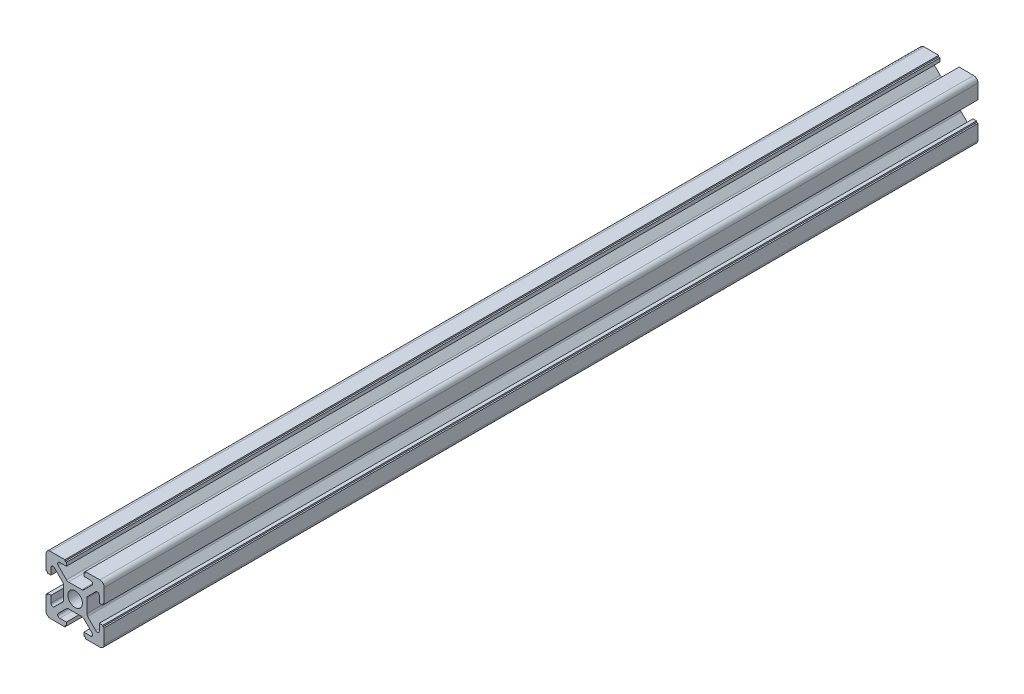
SolidWorks part; units mm, degrees
ref_plane "前视基准面" through (0, 0, 0) normal (0, 0, 1) x (1, 0, 0)
ref_plane "上视基准面" through (0, 0, 0) normal (0, 1, 0) x (1, 0, 0)
ref_plane "右视基准面" through (0, 0, 0) normal (1, 0, 0) x (0, 0, -1)
sketch "草图1" plane through (0, 0, 0) normal (0, 0, 1) x (1, 0, 0)
  line L112 (173.5, -150) -> (168.5, -150)
  line L113 (168.5, -150) -> (168.5, -150.5)
  line L114 (168.5, -150.5) -> (168, -150.5)
  line L115 (168, -150.5) -> (168, -151.7)
  line L116 (168, -151.7) -> (170.2994, -151.7)
  line L117 (170.7944, -152.895) -> (167.1755, -156.5139)
  line L118 (165.3, -156.262) -> (165, -156.55)
  line L119 (165, -156.55) -> (164.7, -156.262)
  line L120 (162.8245, -156.5139) -> (159.2056, -152.895)
  line L121 (159.7006, -151.7) -> (162, -151.7)
  line L122 (162, -151.7) -> (162, -150.5)
  line L123 (162, -150.5) -> (161.5, -150.5)
  line L124 (161.5, -150.5) -> (161.5, -150)
  line L125 (161.5, -150) -> (156.5, -150)
  line L126 (155, -151.5) -> (155, -156.5)
  line L127 (155, -156.5) -> (155.5, -156.5)
  line L128 (155.5, -156.5) -> (155.5, -157)
  line L129 (155.5, -157) -> (156.7, -157)
  line L130 (156.7, -157) -> (156.7, -154.7006)
  line L131 (157.895, -154.2056) -> (161.5139, -157.8245)
  line L132 (161.262, -159.7) -> (161.55, -160)
  line L133 (161.55, -160) -> (161.262, -160.3)
  line L134 (161.5139, -162.1755) -> (157.895, -165.7944)
  line L135 (156.7, -165.2994) -> (156.7, -163)
  line L136 (156.7, -163) -> (155.5, -163)
  line L137 (155.5, -163) -> (155.5, -163.5)
  line L138 (155.5, -163.5) -> (155, -163.5)
  line L139 (155, -163.5) -> (155, -168.5)
  line L140 (156.5, -170) -> (161.5, -170)
  line L141 (161.5, -170) -> (161.5, -169.5)
  line L142 (161.5, -169.5) -> (162, -169.5)
  line L143 (162, -169.5) -> (162, -168.3)
  line L144 (162, -168.3) -> (159.7006, -168.3)
  line L145 (159.2056, -167.105) -> (162.8245, -163.4861)
  line L146 (164.7, -163.738) -> (165, -163.45)
  line L147 (165, -163.45) -> (165.3, -163.738)
  line L148 (167.1755, -163.4861) -> (170.7944, -167.105)
  line L149 (170.2994, -168.3) -> (168, -168.3)
  line L150 (168, -168.3) -> (168, -169.5)
  line L151 (168, -169.5) -> (168.5, -169.5)
  line L152 (168.5, -169.5) -> (168.5, -170)
  line L153 (168.5, -170) -> (173.5, -170)
  line L154 (175, -168.5) -> (175, -163.5)
  line L155 (175, -163.5) -> (174.5, -163.5)
  line L156 (174.5, -163.5) -> (174.5, -163)
  line L157 (174.5, -163) -> (173.3, -163)
  line L158 (173.3, -163) -> (173.3, -165.2994)
  line L159 (172.105, -165.7944) -> (168.4861, -162.1755)
  line L160 (168.738, -160.3) -> (168.45, -160)
  line L161 (168.45, -160) -> (168.738, -159.7)
  line L162 (168.4861, -157.8245) -> (172.105, -154.2056)
  line L163 (173.3, -154.7006) -> (173.3, -157)
  line L164 (173.3, -157) -> (174.5, -157)
  line L165 (174.5, -157) -> (174.5, -156.5)
  line L166 (174.5, -156.5) -> (175, -156.5)
  line L167 (175, -156.5) -> (175, -151.5)
  circle A0 centre (165, -160) radius 2.5
  arc A56 (170.7944, -152.895) -> (170.2994, -151.7) centre (170.2994, -152.4) ccw
  arc A57 (166.6076, -156.612) -> (167.1755, -156.5139) centre (166.8219, -156.1603) ccw
  arc A58 (166.6076, -156.612) -> (165.3, -156.262) centre (165, -160) ccw
  arc A59 (164.7, -156.262) -> (163.3924, -156.612) centre (165, -160) ccw
  arc A60 (162.8245, -156.5139) -> (163.3924, -156.612) centre (163.1781, -156.1603) ccw
  arc A61 (159.7006, -151.7) -> (159.2056, -152.895) centre (159.7006, -152.4) ccw
  arc A62 (156.5, -150) -> (155, -151.5) centre (156.5, -151.5) ccw
  arc A63 (157.895, -154.2056) -> (156.7, -154.7006) centre (157.4, -154.7006) ccw
  arc A64 (161.612, -158.3924) -> (161.5139, -157.8245) centre (161.1603, -158.1781) ccw
  arc A65 (161.612, -158.3924) -> (161.262, -159.7) centre (165, -160) ccw
  arc A66 (161.262, -160.3) -> (161.612, -161.6076) centre (165, -160) ccw
  arc A67 (161.5139, -162.1755) -> (161.612, -161.6076) centre (161.1603, -161.8219) ccw
  arc A68 (156.7, -165.2994) -> (157.895, -165.7944) centre (157.4, -165.2994) ccw
  arc A69 (155, -168.5) -> (156.5, -170) centre (156.5, -168.5) ccw
  arc A70 (159.2056, -167.105) -> (159.7006, -168.3) centre (159.7006, -167.6) ccw
  arc A71 (163.3924, -163.388) -> (162.8245, -163.4861) centre (163.1781, -163.8397) ccw
  arc A72 (163.3924, -163.388) -> (164.7, -163.738) centre (165, -160) ccw
  arc A73 (165.3, -163.738) -> (166.6076, -163.388) centre (165, -160) ccw
  arc A74 (167.1755, -163.4861) -> (166.6076, -163.388) centre (166.8219, -163.8397) ccw
  arc A75 (170.2994, -168.3) -> (170.7944, -167.105) centre (170.2994, -167.6) ccw
  arc A76 (173.5, -170) -> (175, -168.5) centre (173.5, -168.5) ccw
  arc A77 (172.105, -165.7944) -> (173.3, -165.2994) centre (172.6, -165.2994) ccw
  arc A78 (168.388, -161.6076) -> (168.4861, -162.1755) centre (168.8397, -161.8219) ccw
  arc A79 (168.388, -161.6076) -> (168.738, -160.3) centre (165, -160) ccw
  arc A80 (168.738, -159.7) -> (168.388, -158.3924) centre (165, -160) ccw
  arc A81 (168.4861, -157.8245) -> (168.388, -158.3924) centre (168.8397, -158.1781) ccw
  arc A82 (173.3, -154.7006) -> (172.105, -154.2056) centre (172.6, -154.7006) ccw
  arc A83 (175, -151.5) -> (173.5, -150) centre (173.5, -151.5) ccw
extrude "凸台-拉伸1" add sketch "草图1" along normal blind 300
sketch "草图2" plane through (0, 0, 300) normal (0, 0, 1) x (1, 0, 0)
  line L1 (161, -156) -> (169, -156)
  line L2 (161, -156) -> (161, -164)
  line L3 (161, -164) -> (169, -164)
  line L4 (169, -156) -> (169, -164)
  line L5 (161, -156) -> (169, -164) construction
  line L6 (161, -164) -> (169, -156) construction
  circle A0 centre (165, -160) radius 2.5
  point P0 (165, -160)
  dimension "D3" = 5
  dimension "D1" = 8
  dimension "D2" = 8
extrude "凸台-拉伸2" add sketch "草图2" against normal up to surface (300 mm away) up to face at (165, -160, 0)
fillet "圆角1" radius 1 8 edges at (161, -162.6893, 150) (161, -157.3107, 150) (162.3107, -164, 150) (167.6893, -164, 150) (169, -162.6893, 150) (169, -157.3107, 150) (162.3107, -156, 150) (167.6893, -156, 150)
